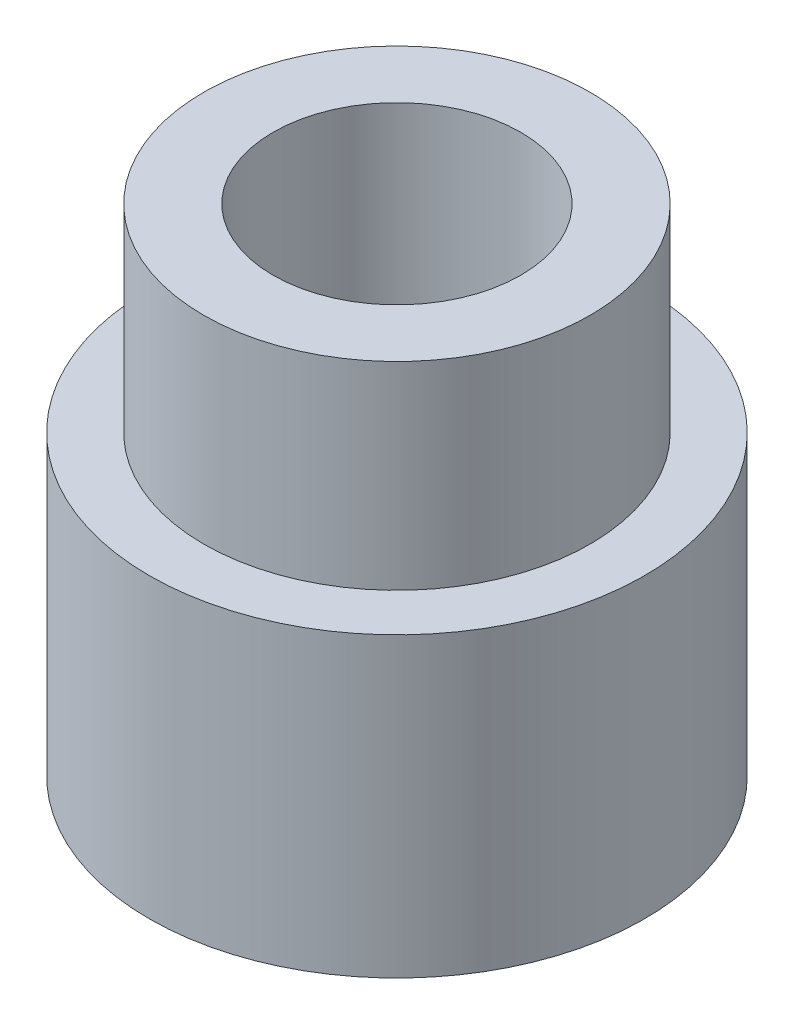
SolidWorks part; units mm, degrees
material "6061-T6 (SS)"
ref_plane "X-Y Datum" through (0, 0, 0) normal (0, 0, 1) x (1, 0, 0)
ref_plane "X-Z Datum" through (0, 0, 0) normal (0, 1, 0) x (1, 0, 0)
ref_plane "Y-Z Datum" through (0, 0, 0) normal (1, 0, 0) x (0, 0, -1)
sketch "Sketch1" plane through (0, 0, 0) normal (0, 1, 0) x (1, 0, 0)
  line L0 (0, 0) -> (0, 31.75) construction
  circle A0 centre (0, 0) radius 31.75
  circle A1 centre (0, 10.16) radius 3.175 construction
  circle A2 centre (0, 0) radius 3.175 construction
  dimension "D1" = 63.5
  dimension "D3" = 6.35
  dimension "D4" = 6.35
  dimension "D2" = 10.16
extrude "Boss-Extrude1" add sketch "Sketch1" along normal blind 63.5
sketch "Sketch2" plane through (0, 63.5, 0) normal (0, 1, 0) x (1, 0, 0)
  circle A0 centre (0, 0) radius 24.765
  circle A1 centre (0, 0) radius 31.75 construction
  circle A2 centre (0, 0) radius 31.75
  dimension "D1" = 49.53
extrude "Cut-Extrude2" cut sketch "Sketch2" against normal blind 25.4
sketch "Sketch3" plane through (0, 63.5, 0) normal (0, 1, 0) x (1, 0, 0)
  circle A0 centre (0, 0) radius 15.875
  dimension "D1" = 31.75
extrude "Cut-Extrude3" cut sketch "Sketch3" against normal blind 50.8
hole_wizard "1/4 (0.25) Diameter Hole1" positions "Sketch8" profile "Sketch9" hole size "1/4" standard "ANSI Inch"
sketch "Sketch8" plane through (0, 0, 0) normal (0, -1, 0) x (-1, 0, 0)
  point P0 (0, 10.16)
  point P16 (0, 0)
sketch "Sketch9" plane through (0, 0, -10.16) normal (1, 0, 0) x (0, 0, -1)
  line L0 (0, 0) -> (0, 14.6077)
  line L1 (0, 14.6077) -> (3.175, 12.7)
  line L2 (3.175, 12.7) -> (3.175, 0)
  line L5 (3.175, 0) -> (0, 0)
  line L10 (0, 14.6077) -> (-3.175, 12.7) construction
  line L11 (0, -6.35) -> (0, 107.95) construction
  dimension "Hole Dia." = 6.35
  dimension "Hole Depth" = 12.7
  dimension "Drill Angle" = 118
pattern_circular "CirPattern1" count 4 over 360 about axis through (0, 0, 0) along (0, 1, 0) of "1/4 (0.25) Diameter Hole1"
